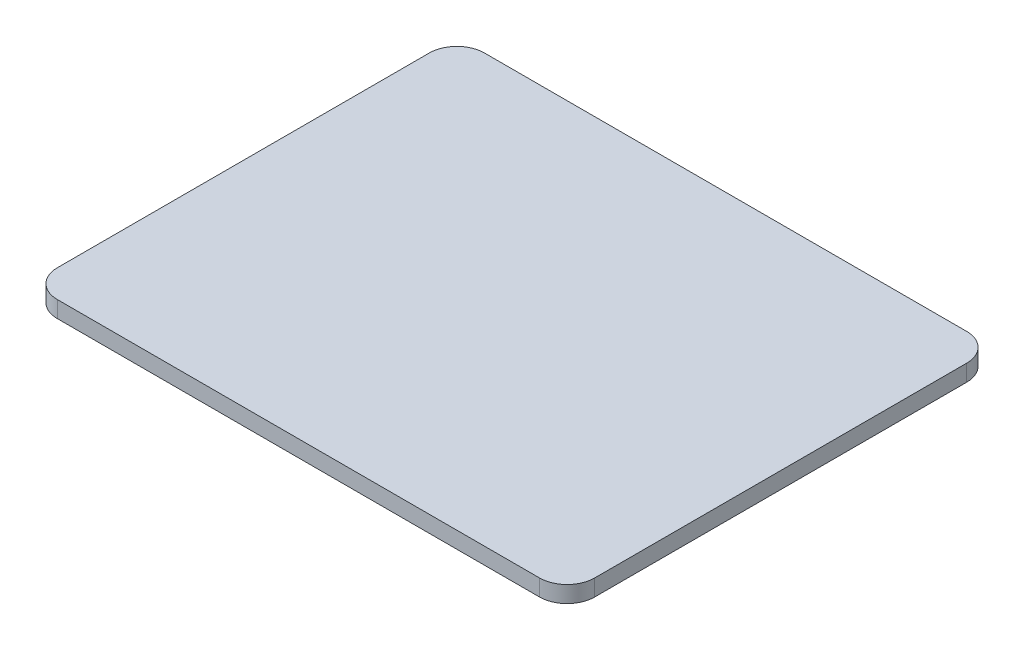
SolidWorks part; units mm, degrees
ref_plane "Front Plane" through (0, 0, 0) normal (0, 0, 1) x (1, 0, 0)
ref_plane "Top Plane" through (0, 0, 0) normal (0, 1, 0) x (1, 0, 0)
ref_plane "Right Plane" through (0, 0, 0) normal (1, 0, 0) x (0, 0, -1)
sketch "Sketch1" plane through (0, 0, 0) normal (0, 1, 0) x (1, 0, 0)
  line L1 (-97.5, 77.5) -> (97.5, 77.5)
  line L2 (-97.5, 77.5) -> (-97.5, -77.5)
  line L3 (-97.5, -77.5) -> (97.5, -77.5)
  line L4 (97.5, 77.5) -> (97.5, -77.5)
  line L5 (-97.5, 77.5) -> (97.5, -77.5) construction
  line L6 (-97.5, -77.5) -> (97.5, 77.5) construction
  point P0 (0, 0)
  dimension "D1" = 155
  dimension "D2" = 195
extrude "Boss-Extrude1" add sketch "Sketch1" along normal blind 6
fillet "Fillet1" radius 10 4 edges at (97.5, 3, 77.5) (97.5, 3, -77.5) (-97.5, 3, 77.5) (-97.5, 3, -77.5)
